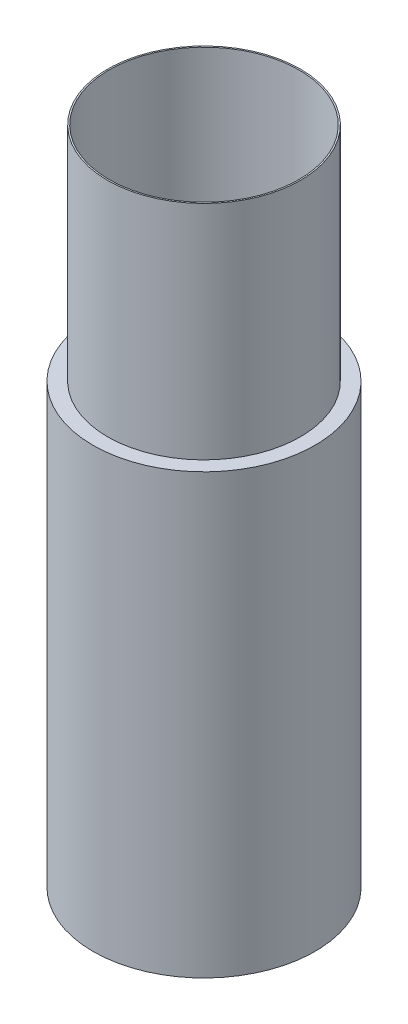
SolidWorks part; units mm, degrees
material "A-Glass Fiber"
ref_plane "Front Plane" through (0, 0, 0) normal (0, 0, 1) x (1, 0, 0)
ref_plane "Top Plane" through (0, 0, 0) normal (0, 1, 0) x (1, 0, 0)
ref_plane "Right Plane" through (0, 0, 0) normal (1, 0, 0) x (0, 0, -1)
sketch "Sketch1" plane through (0, 0, 0) normal (0, 0, 1) x (1, 0, 0)
  line L0 (76, 0) -> (76, 300)
  line L1 (66, 0) -> (66, 300)
  line L2 (76, 300) -> (66, 300)
  line L3 (66, 0) -> (76, 0)
  line L4 (0, 204.6154) -> (0, 85.8935) construction
  dimension "D1" = 76
  dimension "D2" = 300
  dimension "D3" = 10
revolve "Revolve1" add sketch "Sketch1" angle 360 about L4
sketch "Sketch3" plane through (0, 300, 0) normal (0, 1, 0) x (1, 0, 0)
  circle A0 centre (0, 0) radius 66
  circle A1 centre (0, 0) radius 65
  dimension "D1" = 1
extrude "Boss-Extrude1" add sketch "Sketch3" along normal blind 152 and the other way blind 152
